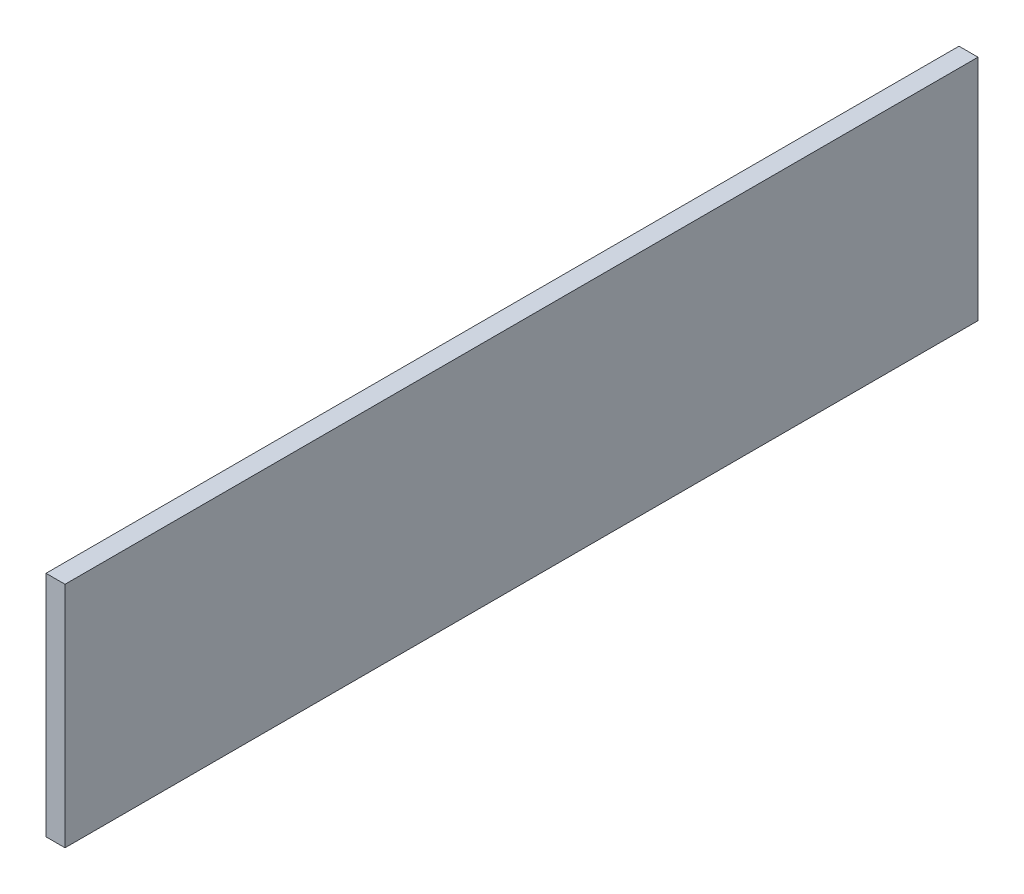
SolidWorks part; units mm, degrees
ref_plane "Front Plane" through (0, 0, 0) normal (0, 0, 1) x (1, 0, 0)
ref_plane "Top Plane" through (0, 0, 0) normal (0, 1, 0) x (1, 0, 0)
ref_plane "Right Plane" through (0, 0, 0) normal (1, 0, 0) x (0, 0, -1)
sketch "Sketch1" plane through (0, 0, 0) normal (1, 0, 0) x (0, 0, -1)
  line L1 (152.4, -38.1) -> (-152.4, -38.1)
  line L2 (152.4, -38.1) -> (152.4, 38.1)
  line L3 (152.4, 38.1) -> (-152.4, 38.1)
  line L4 (-152.4, -38.1) -> (-152.4, 38.1)
  line L5 (152.4, -38.1) -> (-152.4, 38.1) construction
  line L6 (152.4, 38.1) -> (-152.4, -38.1) construction
  point P0 (0, 0)
  dimension "D1" = 76.2
  dimension "D2" = 304.8
extrude "Boss-Extrude1" add sketch "Sketch1" along normal blind 6.35
